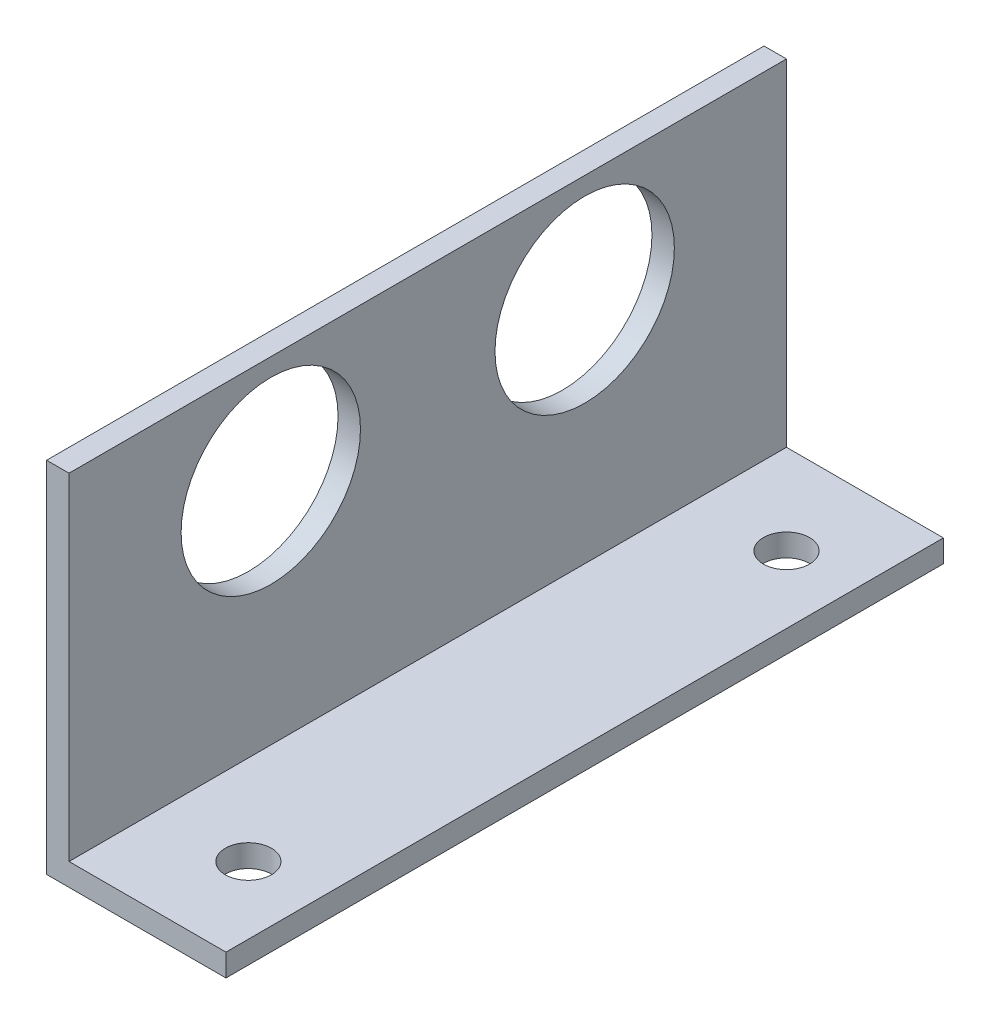
SolidWorks part; units mm, degrees
ref_plane "Front Plane" through (0, 0, 0) normal (0, 0, 1) x (1, 0, 0)
ref_plane "Top Plane" through (0, 0, 0) normal (0, 1, 0) x (1, 0, 0)
ref_plane "Right Plane" through (0, 0, 0) normal (1, 0, 0) x (0, 0, -1)
sketch "Sketch1" plane through (0, 0, 0) normal (0, 0, 1) x (1, 0, 0)
  line L0 (0, 0) -> (12.7, 0)
  line L1 (55, 0) -> (-55, 0) construction
  line L2 (12.7, 0) -> (12.7, 1.5875)
  line L3 (12.7, 1.5875) -> (1.5875, 1.5875)
  line L4 (1.5875, 1.5875) -> (1.5875, 25.4)
  line L5 (1.5875, 25.4) -> (0, 25.4)
  line L6 (0, -55) -> (0, 55) construction
  line L7 (0, 25.4) -> (0, 0)
  dimension "D1" = 1.5875
  dimension "D2" = 12.7
  dimension "D3" = 25.4
extrude "Boss-Extrude1" add sketch "Sketch1" along normal mid plane 50.8
sketch "Sketch3" plane through (0, 0, 0) normal (-1, 0, 0) x (0, 0, 1)
  line L0 (0, 0) -> (0, 17.78) construction
  line L1 (0, 17.78) -> (11.1125, 17.78) construction
  line L2 (0, 17.78) -> (-11.1125, 17.78) construction
  line L3 (25.4, 0) -> (-25.4, 0) construction
  circle A0 centre (11.1125, 17.78) radius 6.35
  circle A1 centre (-11.1125, 17.78) radius 6.35
  dimension "D1" = 12.7
  dimension "D2" = 22.225
  dimension "D3" = 17.78
extrude "Cut-Extrude1" cut sketch "Sketch3" against normal through all
sketch "Sketch5" plane through (0, 1.5875, 0) normal (0, 1, 0) x (1, 0, 0)
  line L0 (1.5875, 0) -> (7.9375, 0) construction
  line L1 (1.5875, -25.4) -> (1.5875, 25.4) construction
  line L2 (7.9375, 0) -> (7.9375, 19.05) construction
  line L3 (7.9375, 0) -> (7.9375, -19.05) construction
  line L4 (12.7, 25.4) -> (1.5875, 25.4) construction
  dimension "D1" = 6.35
  dimension "D2" = 6.35
  dimension "D3" = 38.1
hole_wizard "#4 Clearance Hole1" positions "Sketch10" profile "Sketch9" hole size "#4" standard "ANSI Inch"
sketch "Sketch10" plane through (0, 1.5875, 0) normal (0, 1, 0) x (1, 0, 0)
  point P0 (7.9375, 19.05)
  point P3 (7.9375, -19.05)
sketch "Sketch9" plane through (7.9375, 1.5875, -19.05) normal (1, 0, 0) x (0, 0, 1)
  line L0 (0, 0) -> (0, 4.1556)
  line L1 (0, 4.1556) -> (1.6319, 3.175)
  line L2 (1.6319, 3.175) -> (1.6319, 0)
  line L5 (1.6319, 0) -> (0, 0)
  line L10 (0, 4.1556) -> (-1.632, 3.175) construction
  line L11 (0, -6.35) -> (0, 107.95) construction
  dimension "Hole Dia." = 3.2639
  dimension "Hole Depth" = 3.175
  dimension "Drill Angle" = 118
